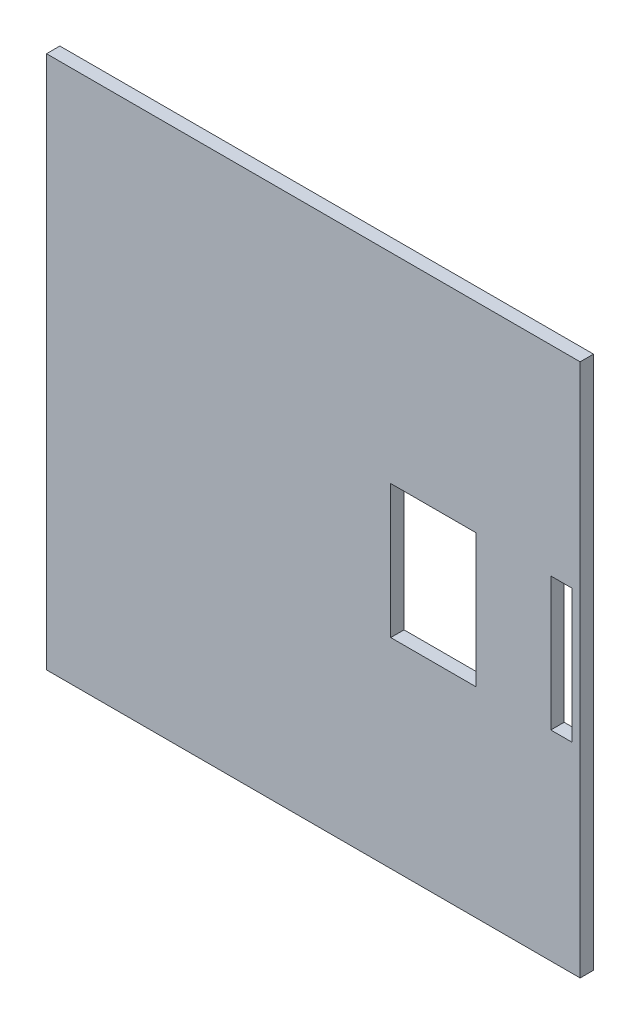
SolidWorks part; units mm, degrees
ref_plane "Plan de face" through (0, 0, 0) normal (0, 0, 1) x (1, 0, 0)
ref_plane "Plan de dessus" through (0, 0, 0) normal (0, 1, 0) x (1, 0, 0)
ref_plane "Plan de droite" through (0, 0, 0) normal (1, 0, 0) x (0, 0, -1)
sketch "Esquisse1" plane through (0, 0, 0) normal (0, 0, 1) x (1, 0, 0)
  line L1 (0, 0) -> (200, 0)
  line L2 (0, 0) -> (0, 200)
  line L3 (0, 200) -> (200, 200)
  line L4 (200, 0) -> (200, 200)
  dimension "D1" = 200
  dimension "D2" = 200
extrude "Boss.-Extru.1" add sketch "Esquisse1" along normal blind 5
sketch "Esquisse2" plane through (0, 0, 5) normal (0, 0, 1) x (1, 0, 0)
  line L0 (200, 0) -> (200, 200) construction
  line L1 (189, 125) -> (197, 125)
  line L2 (189, 125) -> (189, 75)
  line L3 (189, 75) -> (197, 75)
  line L4 (197, 125) -> (197, 75)
  line L5 (200, 100) -> (194, 100) construction
  point P8 (197, 100)
  dimension "D1" = 8
  dimension "D2" = 50
  dimension "D3" = 3
extrude "Enlèv. mat.-Extru.1" cut sketch "Esquisse2" against normal blind 5
sketch "Esquisse3" plane through (0, 0, 5) normal (0, 0, 1) x (1, 0, 0)
  line L0 (189, 125) -> (189, 75) construction
  line L1 (161, 125) -> (129, 125)
  line L2 (161, 125) -> (161, 75)
  line L3 (161, 75) -> (129, 75)
  line L4 (129, 125) -> (129, 75)
  line L5 (189, 125) -> (0, 125) construction
  line L6 (0, 200) -> (0, 0) construction
  dimension "D1" = 28
  dimension "D2" = 32
  dimension "D3" = 50
extrude "Enlèv. mat.-Extru.2" cut sketch "Esquisse3" against normal blind 5
